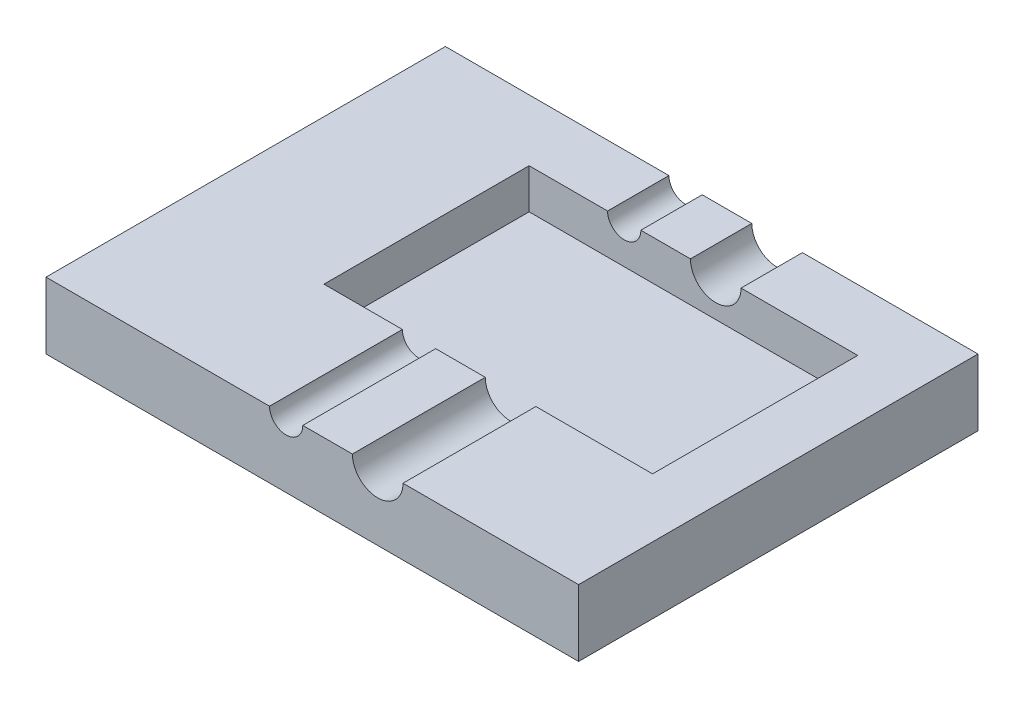
SolidWorks part; units mm, degrees
ref_plane "Front Plane" through (0, 0, 0) normal (0, 0, 1) x (1, 0, 0)
ref_plane "Top Plane" through (0, 0, 0) normal (0, 1, 0) x (1, 0, 0)
ref_plane "Right Plane" through (0, 0, 0) normal (1, 0, 0) x (0, 0, -1)
sketch "Sketch1" plane through (0, 0, 0) normal (0, 1, 0) x (1, 0, 0)
  line L1 (-50.8, -8.038) -> (50.8, -8.038)
  line L2 (-50.8, -8.038) -> (-50.8, 68.162)
  line L3 (-50.8, 68.162) -> (50.8, 68.162)
  line L4 (50.8, -8.038) -> (50.8, 68.162)
  line L5 (-50.8, -8.038) -> (50.8, 68.162) construction
  line L6 (-50.8, 68.162) -> (50.8, -8.038) construction
  point P0 (0, 30.062)
  dimension "D1" = 101.6
  dimension "D2" = 76.2
extrude "Boss-Extrude1" add sketch "Sketch1" along normal blind 12.7
sketch "Sketch4" plane through (0, 12.7, 0) normal (0, 1, 0) x (1, 0, 0)
  line L1 (-23.125, 17.3143) -> (39.5601, 17.3143)
  line L2 (-23.125, 17.3143) -> (-23.125, 56.453)
  line L3 (-23.125, 56.453) -> (39.5601, 56.453)
  line L4 (39.5601, 17.3143) -> (39.5601, 56.453)
  line L5 (-23.125, 17.3143) -> (39.5601, 56.453) construction
  line L6 (-23.125, 56.453) -> (39.5601, 17.3143) construction
  point P0 (8.2175, 36.8836)
extrude "Cut-Extrude2" cut sketch "Sketch4" against normal blind 7.62 contours L1 L4 L3 L2
sketch "Sketch5" plane through (0, 0, 8.038) normal (0, 0, 1) x (1, 0, 0)
  line L0 (-50.8, 12.7) -> (50.8, 12.7) construction
  circle A0 centre (-4.9866, 12.7) radius 3.175
  circle A1 centre (12.4759, 12.7) radius 4.826
  dimension "D1" = 6.35
  dimension "D2" = 9.652
  dimension "D3" = 17.4625
extrude "Cut-Extrude3" cut sketch "Sketch5" against normal through all
